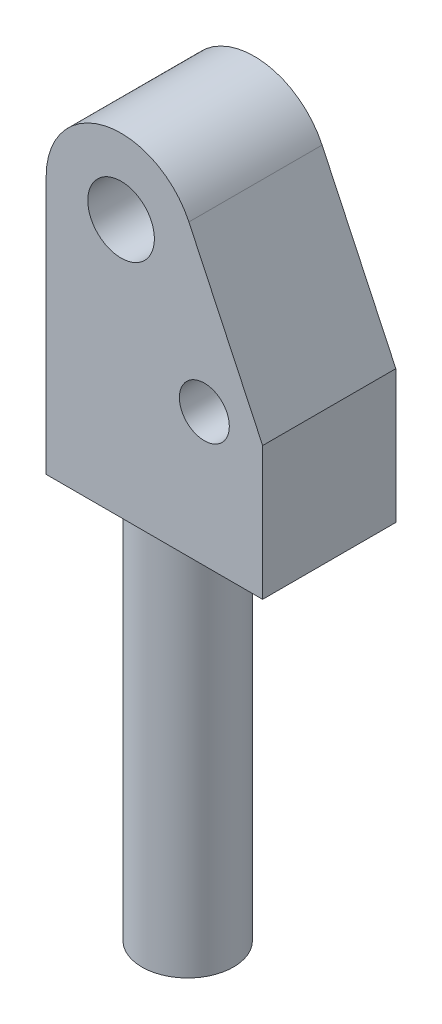
SolidWorks part; units mm, degrees
ref_plane "Front Plane" through (0, 0, 0) normal (0, 0, 1) x (1, 0, 0)
ref_plane "Top Plane" through (0, 0, 0) normal (0, 1, 0) x (1, 0, 0)
ref_plane "Right Plane" through (0, 0, 0) normal (1, 0, 0) x (0, 0, -1)
sketch "Sketch2" plane through (0, 0, 0) normal (0, 1, 0) x (1, 0, 0)
  circle A0 centre (0, 0) radius 5.5
  dimension "D1" = 11
extrude "Boss-Extrude1" add sketch "Sketch2" along normal blind 48
sketch "Sketch3" plane through (0, 0, 0) normal (0, 0, 1) x (1, 0, 0)
  line L0 (0, 48) -> (0, 90.4842) construction
  line L1 (5.5, 48) -> (-5.5, 48) construction
  line L2 (-9, 79) -> (-9, 48)
  line L3 (-9, 48) -> (17, 48)
  line L4 (17, 48) -> (17, 64)
  line L5 (17, 64) -> (8.1443, 82.8302)
  circle A0 centre (0, 79) radius 4
  arc A1 (8.1443, 82.8302) -> (-9, 79) centre (0, 79) ccw
  circle A2 centre (10, 64) radius 3
  point P12 (0, 0)
  point P16 (5.1255, 86.3979)
  dimension "D1" = 6
  dimension "D2" = 8
  dimension "D3" = 18
  dimension "D4" = 7
  dimension "D5" = 16
  dimension "D6" = 15
  dimension "D7" = 26
extrude "Boss-Extrude2" add sketch "Sketch3" along normal mid plane 16
chamfer "Chamfer1" distance 1 angle 45 1 edges at (0, 48, 5.5)
